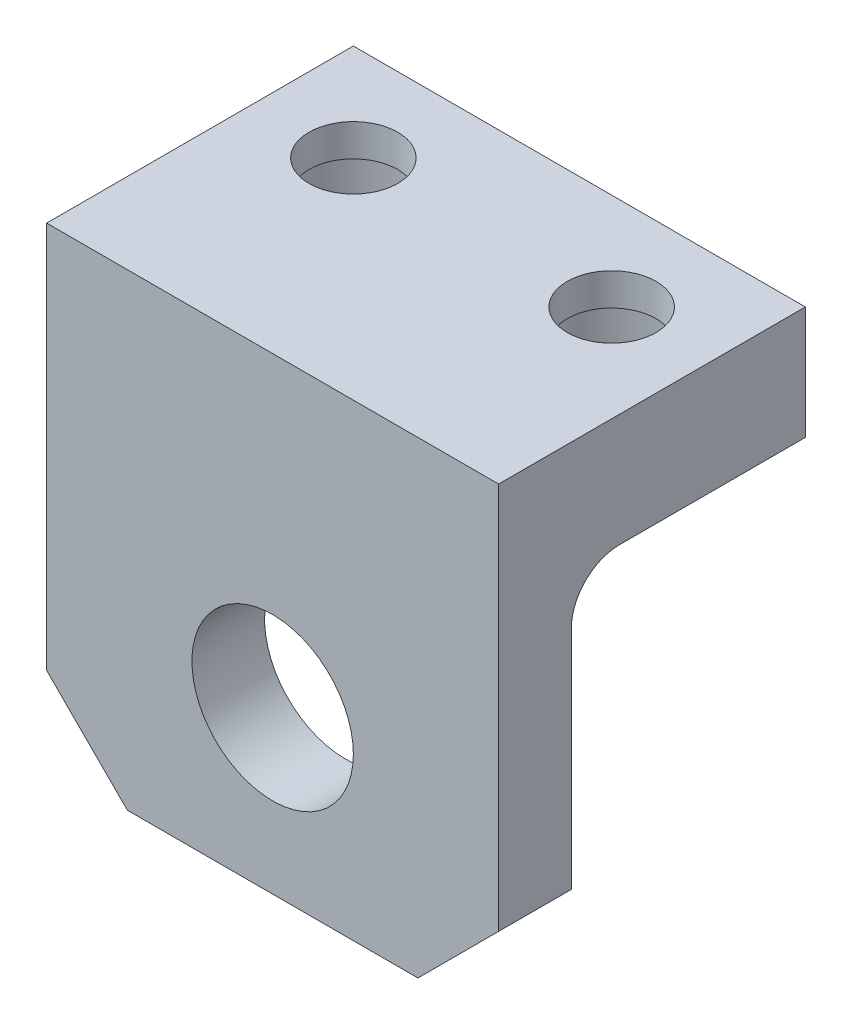
SolidWorks part; units mm, degrees
material "45#"
ref_plane "前视" through (0, 0, 0) normal (0, 0, 1) x (1, 0, 0)
ref_plane "上视" through (0, 0, 0) normal (0, 1, 0) x (1, 0, 0)
ref_plane "右视" through (0, 0, 0) normal (1, 0, 0) x (0, 0, -1)
sketch "草图1" plane through (0, 0, 0) normal (0, 1, 0) x (1, 0, 0)
  line L1 (-14, -9.5) -> (14, -9.5)
  line L2 (-14, -9.5) -> (-14, 9.5)
  line L3 (-14, 9.5) -> (14, 9.5)
  line L4 (14, -9.5) -> (14, 9.5)
  line L5 (-14, -9.5) -> (14, 9.5) construction
  line L6 (-14, 9.5) -> (14, -9.5) construction
  point P0 (0, 0)
  dimension "D1" = 19
  dimension "D2" = 28
extrude "凸台-拉伸1" add sketch "草图1" against normal blind 29
sketch "草图2" plane through (14, 0, 0) normal (1, 0, 0) x (0, 0, -1)
  line L0 (-9.5, -29) -> (-9.5, 0) construction
  line L1 (9.5, -29) -> (-5, -29)
  line L2 (9.5, -29) -> (9.5, -7)
  line L3 (9.5, -7) -> (-2, -7)
  line L4 (-5, -29) -> (-5, -10)
  line L5 (-9.5, 0) -> (9.5, 0) construction
  arc A0 (-2, -7) -> (-5, -10) centre (-2, -10) ccw
  dimension "D3" = 3
  dimension "D1" = 4.5
  dimension "D2" = 7
extrude "切除-拉伸1" cut sketch "草图2" against normal through all
hole_wizard "孔1" positions "草图4" profile "草图3" legacy end condition through all
sketch "草图4" plane through (0, 0, 9.5) normal (0, 0, 1) x (1, 0, 0)
  line L0 (0, -29) -> (0, -19) construction
  line L1 (-14, -29) -> (14, -29) construction
  line L3 (-14, 0) -> (14, 0) construction
  point P0 (0, -19)
  dimension "D1" = 19
sketch "草图3" plane through (0, -19, 9.5) normal (1, 0, 0) x (0, -1, 0)
  line L0 (0, 0) -> (0, 19)
  line L1 (0, 19) -> (5, 19)
  line L2 (5, 19) -> (5, 0)
  line L3 (5, 0) -> (0, 0)
  line L4 (0, 110) -> (0, -10) construction
  dimension "直径" = 10
  dimension "深度" = 19
hole_wizard "打孔尺寸根据内六角圆柱头螺钉的类型1" positions "草图6" profile "草图5" counterbore size "M5" standard "Gb" end condition through all
sketch "草图6" plane through (0, -7, 0) normal (0, -1, 0) x (-1, 0, 0)
  line L0 (0, 9.5) -> (0, -13.0922) construction
  line L1 (14, 9.5) -> (-14, 9.5) construction
  line L3 (14, -9.5) -> (-14, -9.5) construction
  point P0 (8, 3.5)
  point P11 (-8, 3.5)
  dimension "D1" = 16
  dimension "D2" = 13
sketch "草图5" plane through (-8, -7, -3.5) normal (1, 0, 0) x (0, 0, -1)
  line L0 (0, 0) -> (0, 7)
  line L1 (0, 7) -> (2.75, 7)
  line L3 (2.75, 7) -> (2.75, 5)
  line L4 (2.75, 5) -> (5, 5)
  line L5 (5, 5) -> (5, 0)
  line L7 (5, 0) -> (0, 0)
  line L11 (0, -6.35) -> (0, 107.95) construction
  dimension "通孔孔直径" = 5.5
  dimension "通孔孔深度" = 7
  dimension "柱形沉头孔直径" = 10
  dimension "柱形沉头孔深度" = 5
chamfer "倒角1" distance 5 angle 45 2 edges at (14, -29, 7.25) (-14, -29, 7.25)
